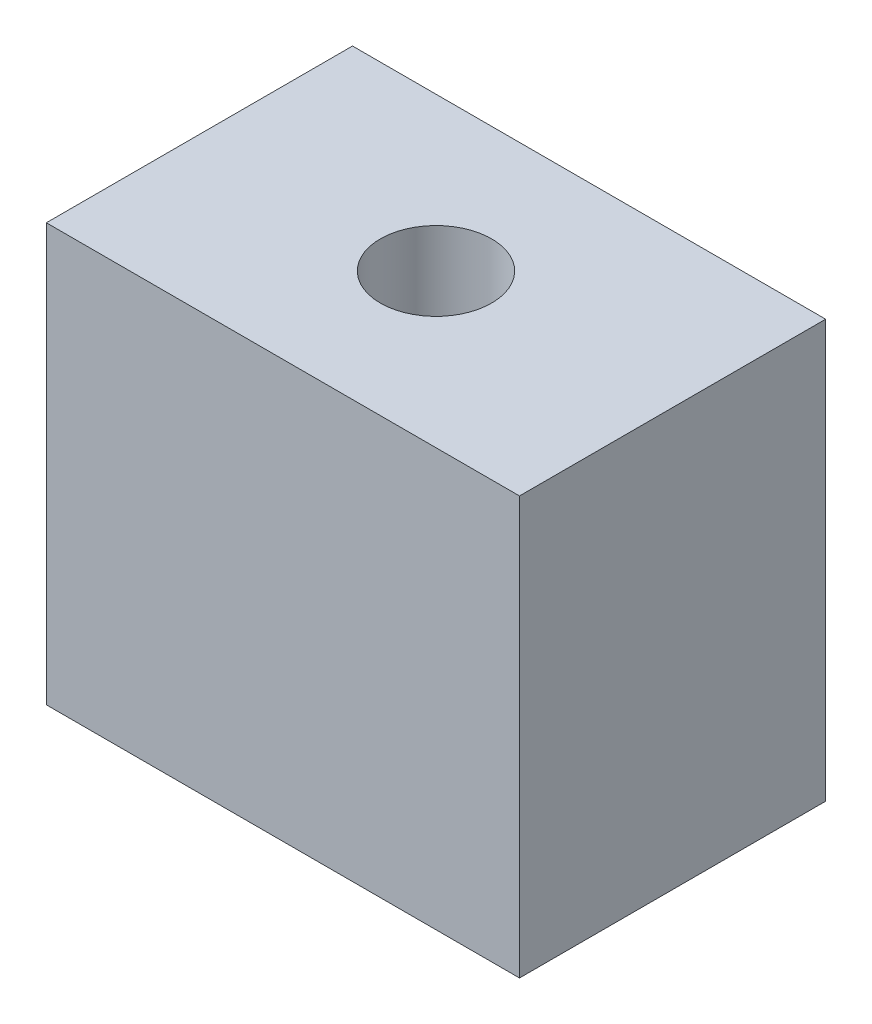
SolidWorks part; units mm, degrees
ref_plane "Front Plane" through (0, 0, 0) normal (0, 0, 1) x (1, 0, 0)
ref_plane "Top Plane" through (0, 0, 0) normal (0, 1, 0) x (1, 0, 0)
ref_plane "Right Plane" through (0, 0, 0) normal (1, 0, 0) x (0, 0, -1)
sketch "Sketch1" plane through (0, 0, 0) normal (0, 0, 1) x (1, 0, 0)
  line L1 (-17, 15) -> (17, 15)
  line L2 (-17, 15) -> (-17, -15)
  line L3 (-17, -15) -> (17, -15)
  line L4 (17, 15) -> (17, -15)
  line L5 (-17, 15) -> (17, -15) construction
  line L6 (-17, -15) -> (17, 15) construction
  point P0 (0, 0)
extrude "Boss-Extrude1" add sketch "Sketch1" along normal blind 22
sketch "Sketch2" plane through (0, 15, 0) normal (0, 1, 0) x (-1, 0, 0)
  line L0 (17, 11) -> (-17, 11) construction
  line L1 (17, 22) -> (17, 0) construction
  line L2 (-17, 22) -> (-17, 0) construction
  circle A0 centre (0, 11) radius 4
extrude "Cut-Extrude1" cut sketch "Sketch2" against normal blind 30
